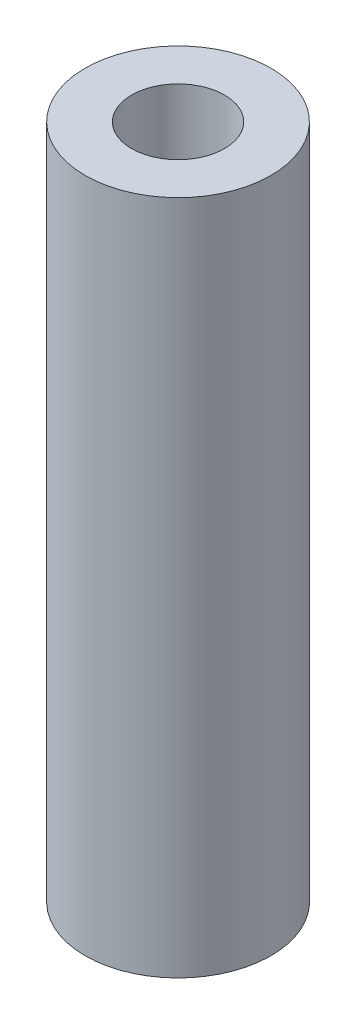
SolidWorks part; units mm, degrees
ref_plane "Front Plane" through (0, 0, 0) normal (0, 0, 1) x (1, 0, 0)
ref_plane "Top Plane" through (0, 0, 0) normal (0, 1, 0) x (1, 0, 0)
ref_plane "Right Plane" through (0, 0, 0) normal (1, 0, 0) x (0, 0, -1)
sketch "Sketch1" plane through (0, 0, 0) normal (0, 1, 0) x (1, 0, 0)
  circle A0 centre (0, 0) radius 11
  circle A1 centre (0, 0) radius 5.5
  dimension "D1" = 22
  dimension "D2" = 11
extrude "Boss-Extrude1" add sketch "Sketch1" along normal blind 80
